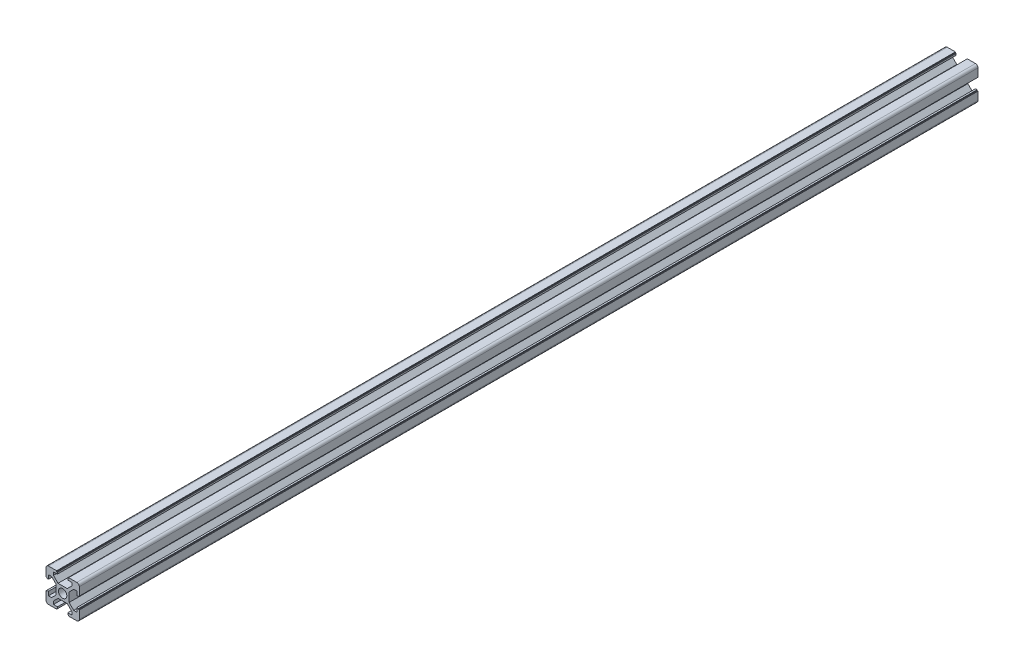
SolidWorks part; units mm, degrees
ref_plane "前视基准面" through (0, 0, 0) normal (0, 0, 1) x (1, 0, 0)
ref_plane "上视基准面" through (0, 0, 0) normal (0, 1, 0) x (1, 0, 0)
ref_plane "右视基准面" through (0, 0, 0) normal (1, 0, 0) x (0, 0, -1)
other "Configuration Table"
sketch "草图1" plane through (0, 0, 0) normal (1, 0, 0) x (0, 0, -1)
  line L0 (0, 0) -> (540, 0)
  dimension "D1" = 540
other "铝型材 20 X 20 X R1.5(1)"
ref_plane "基准面1" through (0, 0, 0) normal (0, 0, -1) x (0, 1, 0)
sketch "Sketch13" plane through (0, 0, 0) normal (0, 0, -1) x (0, 1, 0)
  line L0 (-3.6, 10) -> (-3.6, 9.5)
  line L1 (-3.6, 9.5) -> (-3.1, 9.5)
  line L2 (-3.1, 9.5) -> (-3.1, 8.5)
  line L3 (-3.1, 8.5) -> (-5.5, 8.5)
  line L4 (-8.5, -10) -> (-3.6, -10)
  line L5 (-10, -8.5) -> (-10, -3.6)
  line L6 (8.5, 10) -> (3.6, 10)
  line L7 (10, 8.5) -> (10, 3.6)
  line L8 (0, 14.8756) -> (0, 0) construction
  line L9 (0, 0) -> (14.1675, 0) construction
  line L10 (-5.5, 8.5) -> (-5.5, 6.65)
  line L11 (-5.5, 6.65) -> (-2.75, 3.9)
  line L12 (-2.75, 3.9) -> (2.75, 3.9)
  line L13 (5.5, 6.65) -> (2.75, 3.9)
  line L14 (5.5, 8.5) -> (5.5, 6.65)
  line L15 (3.1, 8.5) -> (5.5, 8.5)
  line L16 (3.1, 9.5) -> (3.1, 8.5)
  line L17 (3.6, 9.5) -> (3.1, 9.5)
  line L18 (3.6, 10) -> (3.6, 9.5)
  line L19 (-3.6, 10) -> (-8.5, 10)
  line L20 (10, 3.6) -> (9.5, 3.6)
  line L21 (9.5, 3.6) -> (9.5, 3.1)
  line L22 (9.5, 3.1) -> (8.5, 3.1)
  line L23 (8.5, 3.1) -> (8.5, 5.5)
  line L24 (8.5, 5.5) -> (6.65, 5.5)
  line L25 (6.65, 5.5) -> (3.9, 2.75)
  line L26 (3.9, 2.75) -> (3.9, -2.75)
  line L27 (6.65, -5.5) -> (3.9, -2.75)
  line L28 (8.5, -5.5) -> (6.65, -5.5)
  line L29 (8.5, -3.1) -> (8.5, -5.5)
  line L30 (9.5, -3.1) -> (8.5, -3.1)
  line L31 (9.5, -3.6) -> (9.5, -3.1)
  line L32 (10, -3.6) -> (9.5, -3.6)
  line L33 (3.6, -10) -> (3.6, -9.5)
  line L34 (3.6, -9.5) -> (3.1, -9.5)
  line L35 (3.1, -9.5) -> (3.1, -8.5)
  line L36 (3.1, -8.5) -> (5.5, -8.5)
  line L37 (5.5, -8.5) -> (5.5, -6.65)
  line L38 (5.5, -6.65) -> (2.75, -3.9)
  line L39 (2.75, -3.9) -> (-2.75, -3.9)
  line L40 (-5.5, -6.65) -> (-2.75, -3.9)
  line L41 (-5.5, -8.5) -> (-5.5, -6.65)
  line L42 (-3.1, -8.5) -> (-5.5, -8.5)
  line L43 (-3.1, -9.5) -> (-3.1, -8.5)
  line L44 (-3.6, -9.5) -> (-3.1, -9.5)
  line L45 (-3.6, -10) -> (-3.6, -9.5)
  line L46 (-10, -3.6) -> (-9.5, -3.6)
  line L47 (-9.5, -3.6) -> (-9.5, -3.1)
  line L48 (-9.5, -3.1) -> (-8.5, -3.1)
  line L49 (-8.5, -3.1) -> (-8.5, -5.5)
  line L50 (-8.5, -5.5) -> (-6.65, -5.5)
  line L51 (-6.65, -5.5) -> (-3.9, -2.75)
  line L52 (-3.9, -2.75) -> (-3.9, 2.75)
  line L53 (-6.65, 5.5) -> (-3.9, 2.75)
  line L54 (-8.5, 5.5) -> (-6.65, 5.5)
  line L55 (-8.5, 3.1) -> (-8.5, 5.5)
  line L56 (-9.5, 3.1) -> (-8.5, 3.1)
  line L57 (-9.5, 3.6) -> (-9.5, 3.1)
  line L58 (-10, 3.6) -> (-9.5, 3.6)
  line L59 (3.6, -10) -> (8.5, -10)
  line L60 (-10, 3.6) -> (-10, 8.5)
  line L61 (10, -3.6) -> (10, -8.5)
  circle A0 centre (0, 0) radius 2.5
  arc A1 (-10, 8.5) -> (-8.5, 10) centre (-8.5, 8.5) cw
  arc A2 (10, 8.5) -> (8.5, 10) centre (8.5, 8.5) ccw
  arc A3 (-8.5, -10) -> (-10, -8.5) centre (-8.5, -8.5) cw
  arc A4 (8.5, -10) -> (10, -8.5) centre (8.5, -8.5) ccw
  point P0 (-10, 0)
  point P1 (10, 0)
  point P2 (0, 10)
  point P3 (0, -10)
  point P4 (0, 0)
  point P5 (-10, -10)
  point P6 (10, -10)
  point P7 (10, 10)
  point P8 (-10, 10)
  point P13 (0, 0)
  point P36 (-10, 10)
  point P39 (10, 10)
  dimension "D1" = 11
  dimension "D2" = 20
  dimension "D3" = 6.2
  dimension "D4" = 7.2
  dimension "D5" = 6.1
  dimension "D6" = 5
  dimension "D7" = 1.5
  dimension "D8" = 45
  dimension "D9" = 0.5
  dimension "D10" = 1
  dimension "D11" = 5.5
